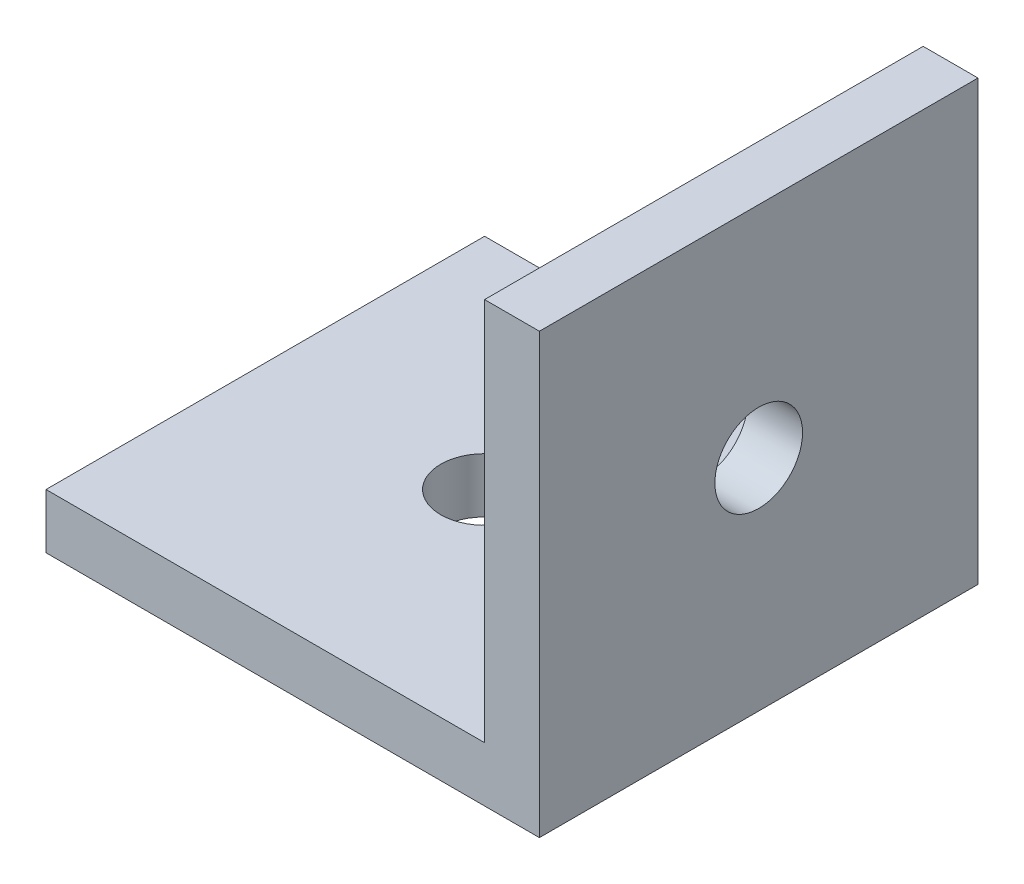
SolidWorks part; units mm, degrees
ref_plane "Front Plane" through (0, 0, 0) normal (0, 0, 1) x (1, 0, 0)
ref_plane "Top Plane" through (0, 0, 0) normal (0, 1, 0) x (1, 0, 0)
ref_plane "Right Plane" through (0, 0, 0) normal (1, 0, 0) x (0, 0, -1)
sketch "Sketch1" plane through (0, 0, 0) normal (0, 1, 0) x (1, 0, 0)
  line L1 (20, -20) -> (-20, -20)
  line L2 (20, -20) -> (20, 20)
  line L3 (20, 20) -> (-20, 20)
  line L4 (-20, -20) -> (-20, 20)
  line L5 (20, -20) -> (-20, 20) construction
  line L6 (20, 20) -> (-20, -20) construction
  circle A0 centre (0, 0) radius 4
  point P0 (0, 0)
  dimension "D3" = 8
  dimension "D1" = 40
  dimension "D2" = 40
extrude "Boss-Extrude1" add sketch "Sketch1" along normal blind 5
sketch "Sketch2" plane through (20, 0, 0) normal (1, 0, 0) x (0, 0, -1)
  line L0 (-20, 40) -> (20, 0) construction
  line L1 (-20, 0) -> (20, 0)
  line L2 (-20, 0) -> (-20, 40)
  line L3 (-20, 40) -> (20, 40)
  line L4 (20, 0) -> (20, 40)
  circle A0 centre (0, 20) radius 4
  dimension "D1" = 40
  dimension "D2" = 40
extrude "Boss-Extrude2" add sketch "Sketch2" along normal blind 5 contours L0 A0 | A0 L0 | L2 L1 L4 L3
